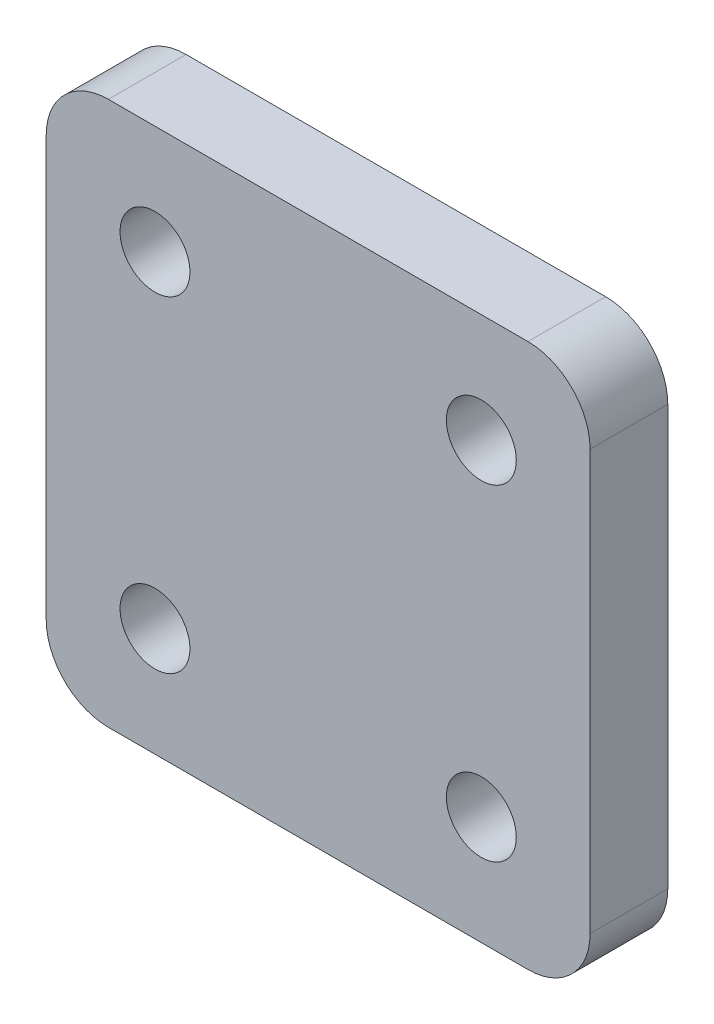
SolidWorks part; units mm, degrees
ref_plane "Front Plane" through (0, 0, 0) normal (0, 0, 1) x (1, 0, 0)
ref_plane "Top Plane" through (0, 0, 0) normal (0, 1, 0) x (1, 0, 0)
ref_plane "Right Plane" through (0, 0, 0) normal (1, 0, 0) x (0, 0, -1)
sketch "Sketch1" plane through (0, 0, 0) normal (0, 0, 1) x (1, 0, 0)
  line L0 (616.2, 257.2) -> (-31, 257.2) construction
  line L1 (0, 257.2) -> (-35, 257.2)
  line L2 (0, 257.2) -> (0, 222.2)
  line L3 (0, 222.2) -> (-35, 222.2)
  line L4 (-35, 257.2) -> (-35, 222.2)
  line L5 (-35, 253.2) -> (-35, 223.8569) construction
  circle A0 centre (-7, 250.2) radius 2.25
  circle A1 centre (-7, 229.2) radius 2.25
  circle A2 centre (-28, 229.2) radius 2.25
  circle A3 centre (-28, 250.2) radius 2.25
  dimension "D1" = 35
  dimension "D2" = 35
extrude "Boss-Extrude1" add sketch "Sketch1" along normal blind 5
fillet "Fillet1" radius 4 4 edges at (0, 222.2, 2.5) (-35, 222.2, 2.5) (0, 257.2, 2.5) (-35, 257.2, 2.5)
sketch "Sketch2" plane through (0, 0, 0) normal (0, 0, -1) x (-1, 0, 0)
  circle A0 centre (17.5, 239.7) radius 9.5
  dimension "D1" = 19
extrude "Cut-Extrude1" cut sketch "Sketch2" against normal blind 3
